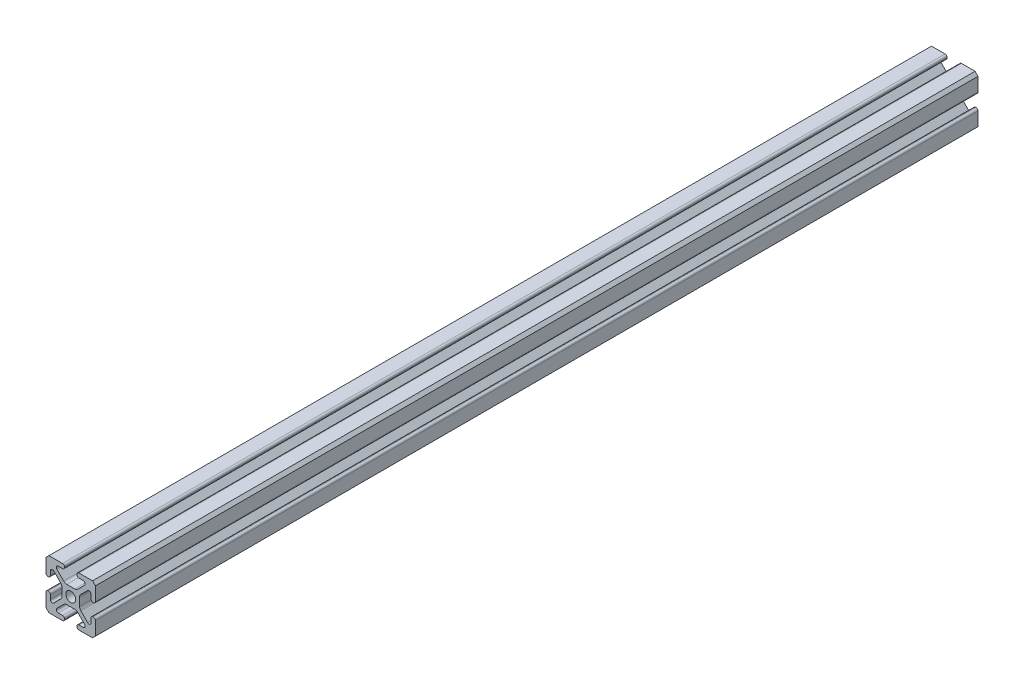
SolidWorks part; units mm, degrees
ref_plane "Front Plane" through (0, 0, 0) normal (0, 0, 1) x (1, 0, 0)
ref_plane "Top Plane" through (0, 0, 0) normal (0, 1, 0) x (1, 0, 0)
ref_plane "Right Plane" through (0, 0, 0) normal (1, 0, 0) x (0, 0, -1)
other "Configuration Table"
sketch "Sketch1" plane through (0, 0, 0) normal (0, 0, 1) x (1, 0, 0)
  line L0 (-11.2, -12.7) -> (-4.2223, -12.7)
  line L1 (-3.2063, -11.684) -> (-3.2063, -11.4407)
  line L2 (-4.2223, -10.4247) -> (-6.4093, -10.4247)
  line L3 (-7.1277, -8.6902) -> (-3.5932, -5.1557)
  line L4 (-2.0306, -4.5085) -> (2.0306, -4.5085)
  line L5 (3.5932, -5.1557) -> (7.1277, -8.6902)
  line L6 (6.4093, -10.4247) -> (4.2223, -10.4247)
  line L7 (3.2063, -11.4407) -> (3.2063, -11.684)
  line L8 (4.2223, -12.7) -> (11.2, -12.7)
  line L9 (11.2, -12.7) -> (12.7, -11.2)
  line L10 (12.7, -11.2) -> (12.7, -4.2223)
  line L11 (11.684, -3.2063) -> (11.4407, -3.2063)
  line L12 (10.4247, -4.2223) -> (10.4247, -6.4093)
  line L13 (8.6902, -7.1277) -> (5.1557, -3.5932)
  line L14 (4.5085, -2.0306) -> (4.5085, 2.0306)
  line L15 (5.1557, 3.5932) -> (8.6902, 7.1277)
  line L16 (10.4247, 6.4093) -> (10.4247, 4.2223)
  line L17 (11.4407, 3.2063) -> (11.684, 3.2063)
  line L18 (12.7, 4.2223) -> (12.7, 11.2)
  line L19 (12.7, 11.2) -> (11.2, 12.7)
  line L20 (11.2, 12.7) -> (4.2223, 12.7)
  line L21 (3.2063, 11.684) -> (3.2063, 11.4407)
  line L22 (4.2223, 10.4247) -> (6.4093, 10.4247)
  line L23 (7.1277, 8.6902) -> (3.5932, 5.1557)
  line L24 (2.0306, 4.5085) -> (-2.0306, 4.5085)
  line L25 (-3.5932, 5.1557) -> (-7.1277, 8.6902)
  line L26 (-6.4093, 10.4247) -> (-4.2223, 10.4247)
  line L27 (-3.2063, 11.4407) -> (-3.2063, 11.684)
  line L28 (-4.2223, 12.7) -> (-11.2, 12.7)
  line L29 (-11.2, 12.7) -> (-12.7, 11.2)
  line L30 (-12.7, 11.2) -> (-12.7, 4.2223)
  line L31 (-11.684, 3.2063) -> (-11.4407, 3.2063)
  line L32 (-10.4247, 4.2223) -> (-10.4247, 6.4093)
  line L33 (-8.6902, 7.1277) -> (-5.1557, 3.5932)
  line L34 (-4.5085, 2.0306) -> (-4.5085, -2.0306)
  line L35 (-5.1557, -3.5932) -> (-8.6902, -7.1277)
  line L36 (-10.4247, -6.4093) -> (-10.4247, -4.2223)
  line L37 (-11.4407, -3.2063) -> (-11.684, -3.2063)
  line L38 (-12.7, -4.2223) -> (-12.7, -11.2)
  line L39 (-12.7, -11.2) -> (-11.2, -12.7)
  arc A0 (-2.555, 0) -> (2.555, 0) centre (0, 0) ccw
  arc A1 (2.555, 0) -> (-2.555, 0) centre (0, 0) ccw
  arc A2 (-4.2223, -12.7) -> (-3.2063, -11.684) centre (-4.2223, -11.684) ccw
  arc A3 (-3.2063, -11.4407) -> (-4.2223, -10.4247) centre (-4.2223, -11.4407) ccw
  arc A4 (-7.1277, -8.6902) -> (-6.4093, -10.4247) centre (-6.4093, -9.4087) ccw
  arc A5 (-2.0306, -4.5085) -> (-3.5932, -5.1557) centre (-2.0306, -6.7183) ccw
  arc A6 (3.5932, -5.1557) -> (2.0306, -4.5085) centre (2.0306, -6.7183) ccw
  arc A7 (7.4253, -9.4087) -> (7.1277, -8.6902) centre (6.4093, -9.4087) ccw
  arc A8 (6.4093, -10.4247) -> (7.4253, -9.4087) centre (6.4093, -9.4087) ccw
  arc A9 (4.2223, -10.4247) -> (3.2063, -11.4407) centre (4.2223, -11.4407) ccw
  arc A10 (3.2063, -11.684) -> (4.2223, -12.7) centre (4.2223, -11.684) ccw
  arc A11 (12.7, -4.2223) -> (11.684, -3.2063) centre (11.684, -4.2223) ccw
  arc A12 (11.4407, -3.2063) -> (10.4247, -4.2223) centre (11.4407, -4.2223) ccw
  arc A13 (8.6902, -7.1277) -> (10.4247, -6.4093) centre (9.4087, -6.4093) ccw
  arc A14 (4.5085, -2.0306) -> (5.1557, -3.5932) centre (6.7183, -2.0306) ccw
  arc A15 (5.1557, 3.5932) -> (4.5085, 2.0306) centre (6.7183, 2.0306) ccw
  arc A16 (9.4087, 7.4253) -> (8.6902, 7.1277) centre (9.4087, 6.4093) ccw
  arc A17 (10.4247, 6.4093) -> (9.4087, 7.4253) centre (9.4087, 6.4093) ccw
  arc A18 (10.4247, 4.2223) -> (11.4407, 3.2063) centre (11.4407, 4.2223) ccw
  arc A19 (11.684, 3.2063) -> (12.7, 4.2223) centre (11.684, 4.2223) ccw
  arc A20 (4.2223, 12.7) -> (3.2063, 11.684) centre (4.2223, 11.684) ccw
  arc A21 (3.2063, 11.4407) -> (4.2223, 10.4247) centre (4.2223, 11.4407) ccw
  arc A22 (7.1277, 8.6902) -> (6.4093, 10.4247) centre (6.4093, 9.4087) ccw
  arc A23 (2.0306, 4.5085) -> (3.5932, 5.1557) centre (2.0306, 6.7183) ccw
  arc A24 (-3.5932, 5.1557) -> (-2.0306, 4.5085) centre (-2.0306, 6.7183) ccw
  arc A25 (-7.4253, 9.4087) -> (-7.1277, 8.6902) centre (-6.4093, 9.4087) ccw
  arc A26 (-6.4093, 10.4247) -> (-7.4253, 9.4087) centre (-6.4093, 9.4087) ccw
  arc A27 (-4.2223, 10.4247) -> (-3.2063, 11.4407) centre (-4.2223, 11.4407) ccw
  arc A28 (-3.2063, 11.684) -> (-4.2223, 12.7) centre (-4.2223, 11.684) ccw
  arc A29 (-12.7, 4.2223) -> (-11.684, 3.2063) centre (-11.684, 4.2223) ccw
  arc A30 (-11.4407, 3.2063) -> (-10.4247, 4.2223) centre (-11.4407, 4.2223) ccw
  arc A31 (-8.6902, 7.1277) -> (-10.4247, 6.4093) centre (-9.4087, 6.4093) ccw
  arc A32 (-4.5085, 2.0306) -> (-5.1557, 3.5932) centre (-6.7183, 2.0306) ccw
  arc A33 (-5.1557, -3.5932) -> (-4.5085, -2.0306) centre (-6.7183, -2.0306) ccw
  arc A34 (-9.4087, -7.4253) -> (-8.6902, -7.1277) centre (-9.4087, -6.4093) ccw
  arc A35 (-10.4247, -6.4093) -> (-9.4087, -7.4253) centre (-9.4087, -6.4093) ccw
  arc A36 (-10.4247, -4.2223) -> (-11.4407, -3.2063) centre (-11.4407, -4.2223) ccw
  arc A37 (-11.684, -3.2063) -> (-12.7, -4.2223) centre (-11.684, -4.2223) ccw
extrude "Boss-Extrude1" add sketch "Sketch1" along normal blind 453.48
equation "\"Extrusion Length\"= 24"
